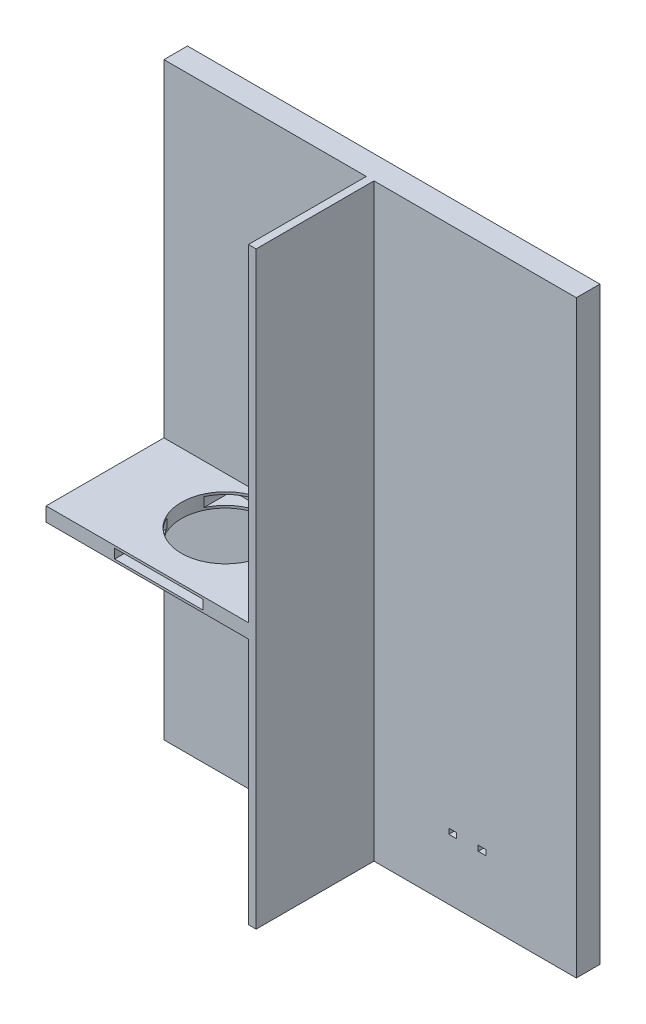
SolidWorks part; units mm, degrees
ref_plane "Ön Düzlem" through (0, 0, 0) normal (0, 0, 1) x (1, 0, 0)
ref_plane "Üst Düzlem" through (0, 0, 0) normal (0, 1, 0) x (1, 0, 0)
ref_plane "Sağ Düzlem" through (0, 0, 0) normal (1, 0, 0) x (0, 0, -1)
sketch "Çizim1" plane through (0, 0, 0) normal (0, 0, 1) x (1, 0, 0)
  line L1 (0, 0) -> (35, 0)
  line L2 (0, 0) -> (0, 50)
  line L3 (0, 50) -> (35, 50)
  line L4 (35, 0) -> (35, 50)
  line L5 (8, 5.4034) -> (8.6, 5.4034)
  line L6 (8, 5.4034) -> (8, 6.0034)
  line L7 (8, 6.0034) -> (8.6, 6.0034)
  line L8 (8.6, 5.4034) -> (8.6, 6.0034)
  line L9 (8, 5.4034) -> (8.6, 6.0034) construction
  line L10 (8, 6.0034) -> (8.6, 5.4034) construction
  line L11 (11.14, 6.0034) -> (10.54, 6.0034)
  line L12 (11.14, 6.0034) -> (11.14, 5.4034)
  line L13 (11.14, 5.4034) -> (10.54, 5.4034)
  line L14 (10.54, 6.0034) -> (10.54, 5.4034)
  line L15 (11.14, 6.0034) -> (10.54, 5.4034) construction
  line L16 (11.14, 5.4034) -> (10.54, 6.0034) construction
  line L17 (27.325, 5.6) -> (26.675, 5.6)
  line L18 (27.325, 5.6) -> (27.325, 5.15)
  line L19 (27.325, 5.15) -> (26.675, 5.15)
  line L20 (26.675, 5.6) -> (26.675, 5.15)
  line L21 (27.325, 5.6) -> (26.675, 5.15) construction
  line L22 (27.325, 5.15) -> (26.675, 5.6) construction
  line L23 (24.825, 5.15) -> (24.175, 5.15)
  line L24 (24.825, 5.15) -> (24.825, 5.6)
  line L25 (24.825, 5.6) -> (24.175, 5.6)
  line L26 (24.175, 5.15) -> (24.175, 5.6)
  line L27 (24.825, 5.15) -> (24.175, 5.6) construction
  line L28 (24.825, 5.6) -> (24.175, 5.15) construction
  point P5 (8.3, 5.7034)
  point P10 (10.84, 5.7034)
  point P15 (27, 5.375)
  point P20 (24.5, 5.375)
  dimension "D1" = 35
  dimension "D2" = 50
  dimension "D3" = 0.6
  dimension "D4" = 0.6
  dimension "D5" = 0.6
  dimension "D6" = 0.6
  dimension "D7" = 2.54
  dimension "D8" = 8
  dimension "D9" = 5.4034
  dimension "D10" = 11.14
  dimension "D11" = 0.45
  dimension "D12" = 0.65
  dimension "D13" = 8
  dimension "D14" = 5.6
  dimension "D15" = 2.5
  dimension "D16" = 0.65
  dimension "D17" = 0.45
  dimension "D18" = 5.6
extrude "Yükseklik-Ekstrüzyon1" add sketch "Çizim1" along normal blind 2
sketch "Çizim2" plane through (0, 0, 2) normal (0, 0, 1) x (1, 0, 0)
  line L0 (0, 0) -> (35, 0) construction
  line L1 (17.175, 50) -> (17.825, 50)
  line L2 (17.175, 50) -> (17.175, 0)
  line L3 (17.175, 0) -> (17.825, 0)
  line L4 (17.825, 50) -> (17.825, 0)
  line L5 (17.175, 50) -> (17.825, 0) construction
  line L6 (17.175, 0) -> (17.825, 50) construction
  line L7 (0, 50) -> (0, 0) construction
  point P0 (17.5, 25)
  dimension "D1" = 50
  dimension "D2" = 0.65
  dimension "D3" = 17.175
extrude "Yükseklik-Ekstrüzyon2" add sketch "Çizim2" along normal blind 10
sketch "Çizim3" plane through (17.175, 0, 0) normal (-1, 0, 0) x (0, 0, 1)
  line L0 (12, 50) -> (12, 0) construction
  line L1 (12, 21) -> (2, 21)
  line L2 (12, 21) -> (12, 22.2)
  line L3 (12, 22.2) -> (2, 22.2)
  line L4 (2, 21) -> (2, 22.2)
  line L5 (2, 50) -> (2, 0) construction
  point P10 (12, 0)
  dimension "D1" = 21
  dimension "D2" = 1.2
extrude "Yükseklik-Ekstrüzyon3" add sketch "Çizim3" along normal through all
sketch "Çizim4" plane through (0, 0, 12) normal (0, 0, 1) x (1, 0, 0)
  line L0 (0, 21) -> (17.175, 21) construction
  line L1 (5.82, 21.2) -> (13.32, 21.2)
  line L2 (5.82, 21.2) -> (5.82, 22)
  line L3 (5.82, 22) -> (13.32, 22)
  line L4 (13.32, 21.2) -> (13.32, 22)
  line L8 (0, 21) -> (0, 22.2) construction
  line L9 (9.57, 23.1964) -> (9.57, -1.1269) construction
  line L14 (11.14, 5.4034) -> (11.14, 6.0034) construction
  point P8 (0, 21.6)
  dimension "D1" = 0.8
  dimension "D2" = 0.2
  dimension "D3" = 7.5
  dimension "D4" = 13.32
  dimension "D5" = 1.57
extrude "Kes-Ekstrüzyon1" cut sketch "Çizim4" against normal blind 10
sketch "Çizim5" plane through (0, 21, 0) normal (0, -1, 0) x (1, 0, 0)
  line L0 (0, 2) -> (17.175, 2) construction
  ellipse E0 centre (9.2248, 6) end of major axis (5.4748, 6) minor radius 3.75
  dimension "D1" = 7.5
  dimension "D2" = 7.5
  dimension "D3" = 4
extrude "Kes-Ekstrüzyon2" cut sketch "Çizim5" against normal up to next
